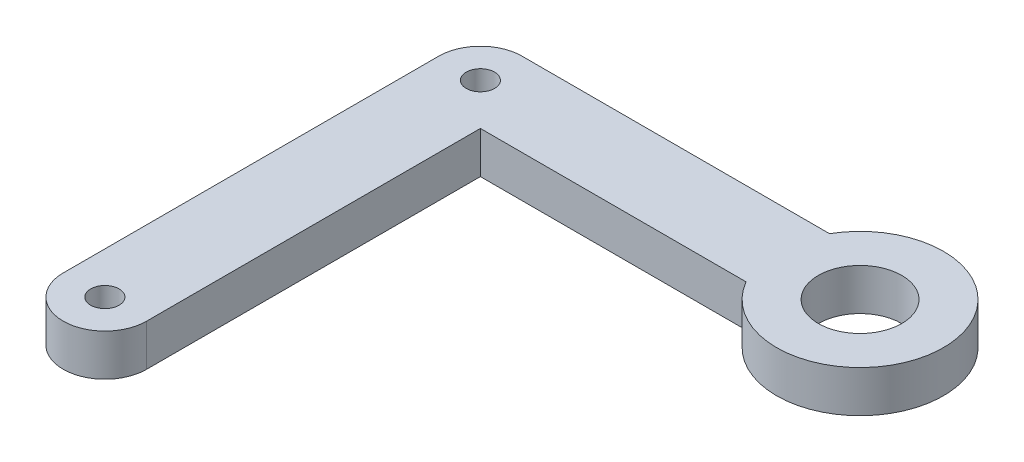
SolidWorks part; units mm, degrees
ref_plane "Front Plane" through (0, 0, 0) normal (0, 0, 1) x (1, 0, 0)
ref_plane "Top Plane" through (0, 0, 0) normal (0, 1, 0) x (1, 0, 0)
ref_plane "Right Plane" through (0, 0, 0) normal (1, 0, 0) x (0, 0, -1)
sketch "Sketch1" plane through (0, 0, 0) normal (0, 1, 0) x (1, 0, 0)
  line L0 (0, 0) -> (0, 45) construction
  line L1 (-5, 0) -> (-5, 45)
  line L2 (5, 0) -> (5, 45)
  arc A0 (-5, 0) -> (5, 0) centre (0, 0) ccw
  arc A1 (5, 45) -> (-5, 45) centre (0, 45) ccw
  circle A2 centre (0, 0) radius 1.7
  circle A3 centre (0, 45) radius 1.7
  point P3 (0, 22.5)
  dimension "D1" = 5
  dimension "D2" = 3.4
  dimension "D3" = 3.4
  dimension "D4" = 45
extrude "Boss-Extrude1" add sketch "Sketch1" along normal blind 5
sketch "Sketch2" plane through (0, 0, 0) normal (0, -1, 0) x (1, 0, 0)
  line L0 (0, -45) -> (45.5, -45) construction
  line L1 (0, -40) -> (45.5, -40)
  line L2 (0, -50) -> (45.5, -50)
  arc A0 (0, -40) -> (0, -50) centre (0, -45) ccw
  arc A1 (45.5, -50) -> (45.5, -40) centre (45.5, -45) ccw
  circle A2 centre (45.5, -45) radius 1.7
  circle A4 centre (0, -45) radius 1.7
  point P3 (22.75, -45)
  dimension "D1" = 5
  dimension "D3" = 3.4
  dimension "D4" = 3.4
  dimension "D2" = 45.5
extrude "Boss-Extrude2" add sketch "Sketch2" against normal blind 5
sketch "Sketch3" plane through (0, 0, 0) normal (0, -1, 0) x (1, 0, 0)
  circle A0 centre (45.5, -45) radius 10
  circle A1 centre (45.5, -45) radius 5
  dimension "D1" = 10
  dimension "D2" = 20
extrude "Boss-Extrude3" add sketch "Sketch3" against normal blind 5
sketch "Sketch4" plane through (0, 0, 0) normal (0, -1, 0) x (1, 0, 0)
  circle A0 centre (45.5, -45) radius 5
  dimension "D1" = 10
extrude "Cut-Extrude1" cut sketch "Sketch4" against normal blind 5
